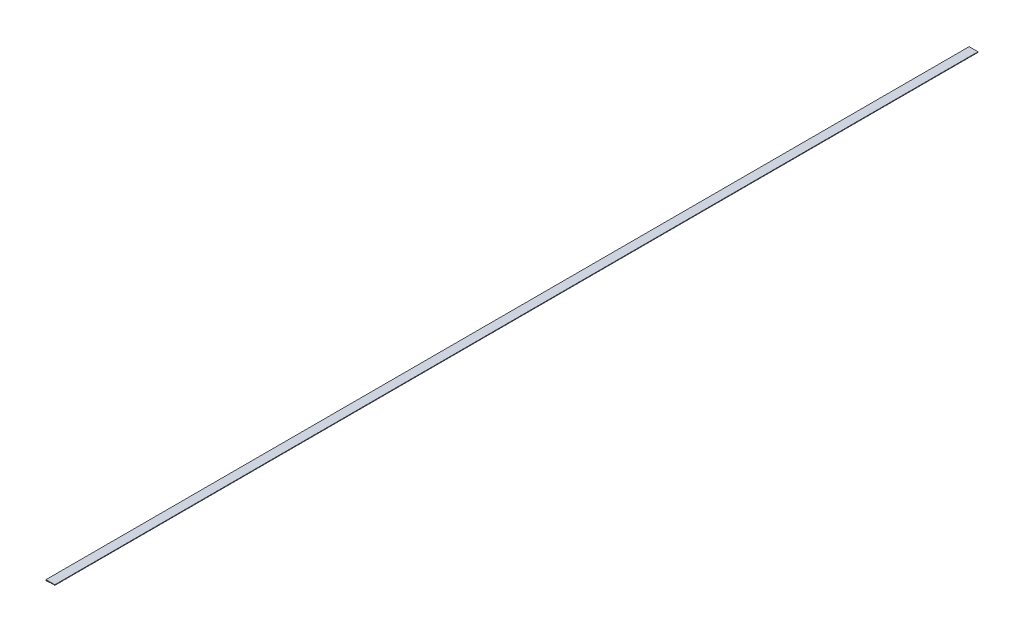
SolidWorks part; units mm, degrees
material "ASTM A500 Grade B Steel"
ref_plane "Front Plane" through (0, 0, 0) normal (0, 0, 1) x (1, 0, 0)
ref_plane "Top Plane" through (0, 0, 0) normal (0, 1, 0) x (1, 0, 0)
ref_plane "Right Plane" through (0, 0, 0) normal (1, 0, 0) x (0, 0, -1)
sketch "Sketch2" plane through (0, 0, 0) normal (0, 0, 1) x (1, 0, 0)
  line L0 (-7.6194, 25.4) -> (-32.6194, 23.2128)
  line L1 (-2103.2445, -157.9434) -> (-7.6194, 25.4) construction
  line L2 (17.3806, 25.4) -> (-7.6194, 25.4)
  line L6 (17.3806, 25.4) -> (17.3806, 28.575)
  line L7 (17.3806, 28.575) -> (-32.6194, 28.575)
  line L8 (-32.6194, 28.575) -> (-32.6194, 23.2128)
  dimension "D1" = 25
  dimension "D2" = 25
  dimension "D3" = 3.175
extrude "Boss-Extrude1" add sketch "Sketch2" against normal up to surface (5214.4 mm away)
